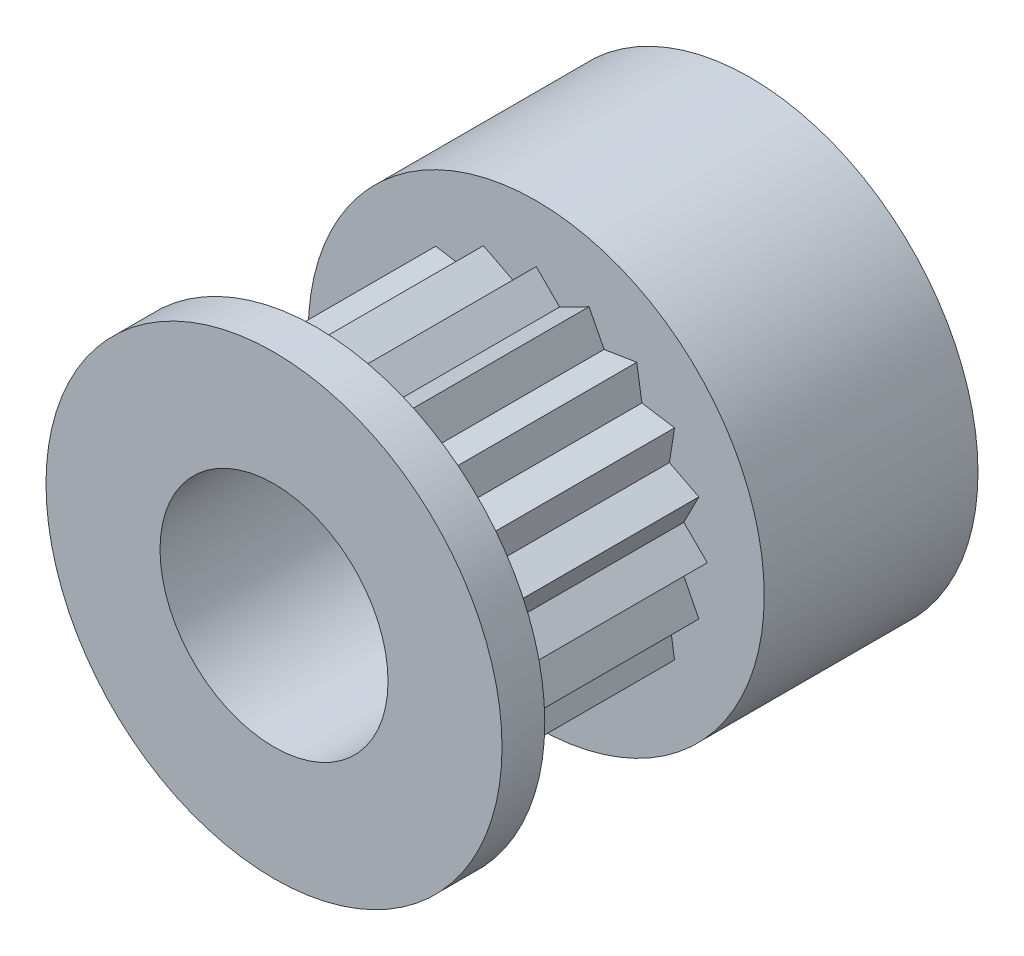
SolidWorks part; units mm, degrees
ref_plane "Front Plane" through (0, 0, 0) normal (0, 0, 1) x (1, 0, 0)
ref_plane "Top Plane" through (0, 0, 0) normal (0, 1, 0) x (1, 0, 0)
ref_plane "Right Plane" through (0, 0, 0) normal (1, 0, 0) x (0, 0, -1)
sketch "Sketch1" plane through (0, 0, 0) normal (0, 0, 1) x (1, 0, 0)
  circle A0 centre (0, 0) radius 8
extrude "Boss-Extrude1" add sketch "Sketch1" along normal blind 7.5
sketch "Sketch2" plane through (0, 0, 7.5) normal (0, 0, 1) x (1, 0, 0)
  line L0 (-0.8204, 5.1796) -> (0, 6)
  line L1 (0, 6) -> (0.8204, 5.1796)
  line L2 (0.8204, 5.1796) -> (1.8541, 5.7063)
  line L3 (1.8541, 5.7063) -> (2.3808, 4.6726)
  line L4 (2.3808, 4.6726) -> (3.5267, 4.8541)
  line L5 (3.5267, 4.8541) -> (3.7082, 3.7082)
  line L6 (3.7082, 3.7082) -> (4.8541, 3.5267)
  line L7 (4.8541, 3.5267) -> (4.6726, 2.3808)
  line L8 (4.6726, 2.3808) -> (5.7063, 1.8541)
  line L9 (5.7063, 1.8541) -> (5.1796, 0.8204)
  line L10 (5.1796, 0.8204) -> (6, 0)
  line L11 (6, 0) -> (5.1796, -0.8204)
  line L12 (5.1796, -0.8204) -> (5.7063, -1.8541)
  line L13 (5.7063, -1.8541) -> (4.6726, -2.3808)
  line L14 (4.6726, -2.3808) -> (4.8541, -3.5267)
  line L15 (4.8541, -3.5267) -> (3.7082, -3.7082)
  line L16 (3.7082, -3.7082) -> (3.5267, -4.8541)
  line L17 (3.5267, -4.8541) -> (2.3808, -4.6726)
  line L18 (2.3808, -4.6726) -> (1.8541, -5.7063)
  line L19 (1.8541, -5.7063) -> (0.8204, -5.1796)
  line L20 (0.8204, -5.1796) -> (0, -6)
  line L21 (0, -6) -> (-0.8204, -5.1796)
  line L22 (-0.8204, -5.1796) -> (-1.8541, -5.7063)
  line L23 (-1.8541, -5.7063) -> (-2.3808, -4.6726)
  line L24 (-2.3808, -4.6726) -> (-3.5267, -4.8541)
  line L25 (-3.5267, -4.8541) -> (-3.7082, -3.7082)
  line L26 (-3.7082, -3.7082) -> (-4.8541, -3.5267)
  line L27 (-4.8541, -3.5267) -> (-4.6726, -2.3808)
  line L28 (-4.6726, -2.3808) -> (-5.7063, -1.8541)
  line L29 (-5.7063, -1.8541) -> (-5.1796, -0.8204)
  line L30 (-5.1796, -0.8204) -> (-6, 0)
  line L31 (-6, 0) -> (-5.1796, 0.8204)
  line L32 (-5.1796, 0.8204) -> (-5.7063, 1.8541)
  line L33 (-5.7063, 1.8541) -> (-4.6726, 2.3808)
  line L34 (-4.6726, 2.3808) -> (-4.8541, 3.5267)
  line L35 (-4.8541, 3.5267) -> (-3.7082, 3.7082)
  line L36 (-3.7082, 3.7082) -> (-3.5267, 4.8541)
  line L37 (-3.5267, 4.8541) -> (-2.3808, 4.6726)
  line L38 (-2.3808, 4.6726) -> (-1.8541, 5.7063)
  line L39 (-1.8541, 5.7063) -> (-0.8204, 5.1796)
  point P0 (0, 6)
  point P65 (0, 0)
  dimension "D1" = 6
  dimension "D2" = 1.1602
  dimension "D4" = 90
  dimension "D3" = 20
extrude "Boss-Extrude2" add sketch "Sketch2" along normal blind 7.7
sketch "Sketch3" plane through (0, 0, 15.2) normal (0, 0, 1) x (1, 0, 0)
  circle A0 centre (0, 0) radius 8
extrude "Boss-Extrude3" add sketch "Sketch3" along normal blind 1.5
sketch "Sketch4" plane through (0, 0, 16.7) normal (0, 0, 1) x (1, 0, 0)
  circle A0 centre (0, 0) radius 4
extrude "Cut-Extrude2" cut sketch "Sketch4" against normal blind 17.5
